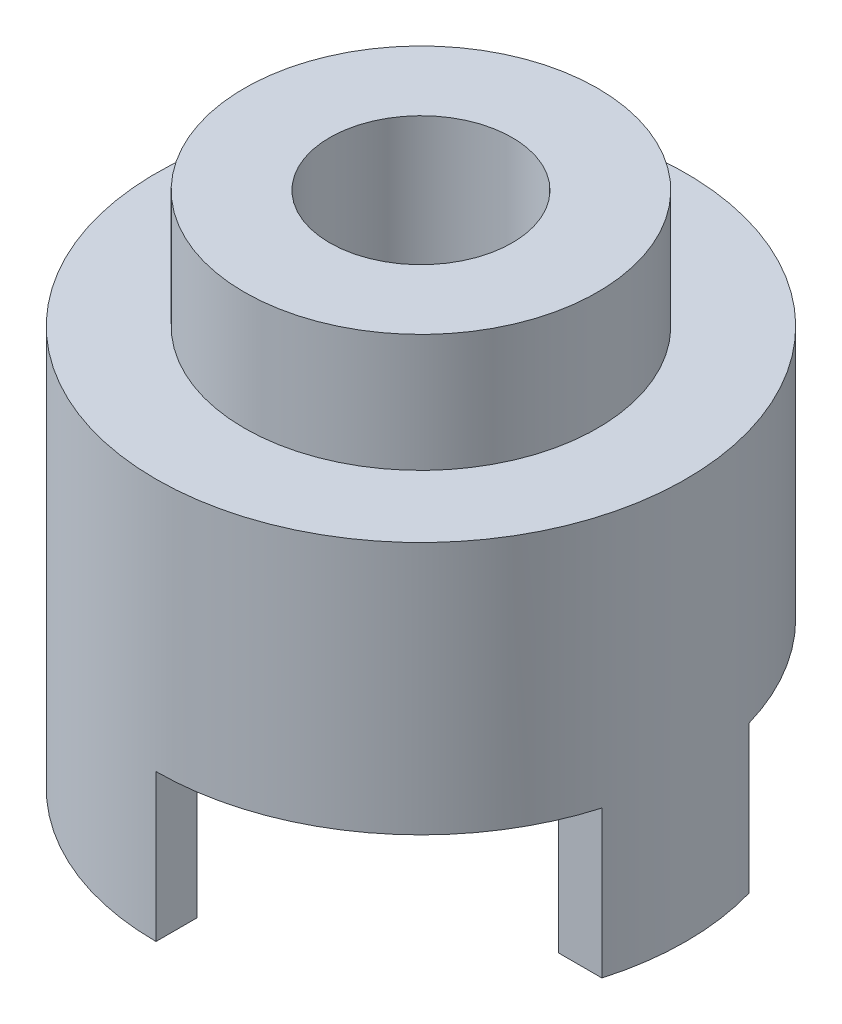
SolidWorks part; units mm, degrees
ref_plane "Front Plane" through (0, 0, 0) normal (0, 0, 1) x (1, 0, 0)
ref_plane "Top Plane" through (0, 0, 0) normal (0, 1, 0) x (1, 0, 0)
ref_plane "Right Plane" through (0, 0, 0) normal (1, 0, 0) x (0, 0, -1)
sketch "Sketch1" plane through (0, 0, 0) normal (0, 1, 0) x (1, 0, 0)
  circle A0 centre (0, 0) radius 4.5
  dimension "D1" = 9
extrude "Boss-Extrude1" add sketch "Sketch1" along normal blind 4.3
sketch "Sketch2" plane through (0, 4.3, 0) normal (0, 1, 0) x (1, 0, 0)
  circle A0 centre (0, 0) radius 3
  dimension "D1" = 6
extrude "Boss-Extrude2" add sketch "Sketch2" along normal blind 2
sketch "Sketch3" plane through (0, 6.3, 0) normal (0, 1, 0) x (1, 0, 0)
  circle A0 centre (0, 0) radius 1.55
  dimension "D1" = 3.1
extrude "Cut-Extrude1" cut sketch "Sketch3" against normal through all
sketch "Sketch4" plane through (0, 0, 0) normal (0, -1, 0) x (1, 0, 0)
  circle A0 centre (0, 0) radius 3.8
  circle A1 centre (0, 0) radius 4.5
  circle A2 centre (0, 0) radius 4.5 construction
  dimension "D1" = 7.6
extrude "Boss-Extrude3" add sketch "Sketch4" along normal blind 2.5
sketch "Sketch5" plane through (0, 0, 0) normal (0, -1, 0) x (1, 0, 0)
  line L0 (0, 0) -> (0, 5.8093)
  line L1 (0, 5.8093) -> (6.5564, 5.8093)
  line L2 (6.5564, 5.8093) -> (6.5564, 1.25)
  line L3 (6.5564, 1.25) -> (2.958, 1.25)
  line L4 (2.958, 1.25) -> (2.958, -1.25)
  line L5 (2.958, -1.25) -> (6.5564, -1.25)
  line L6 (6.5564, -1.25) -> (6.5564, -5.8093)
  line L7 (6.5564, -5.8093) -> (0, -5.8093)
  line L8 (0, -5.8093) -> (0, 0)
  point P4 (2.958, 0)
  dimension "D1" = 2.5
extrude "Cut-Extrude2" cut sketch "Sketch5" along normal through all
